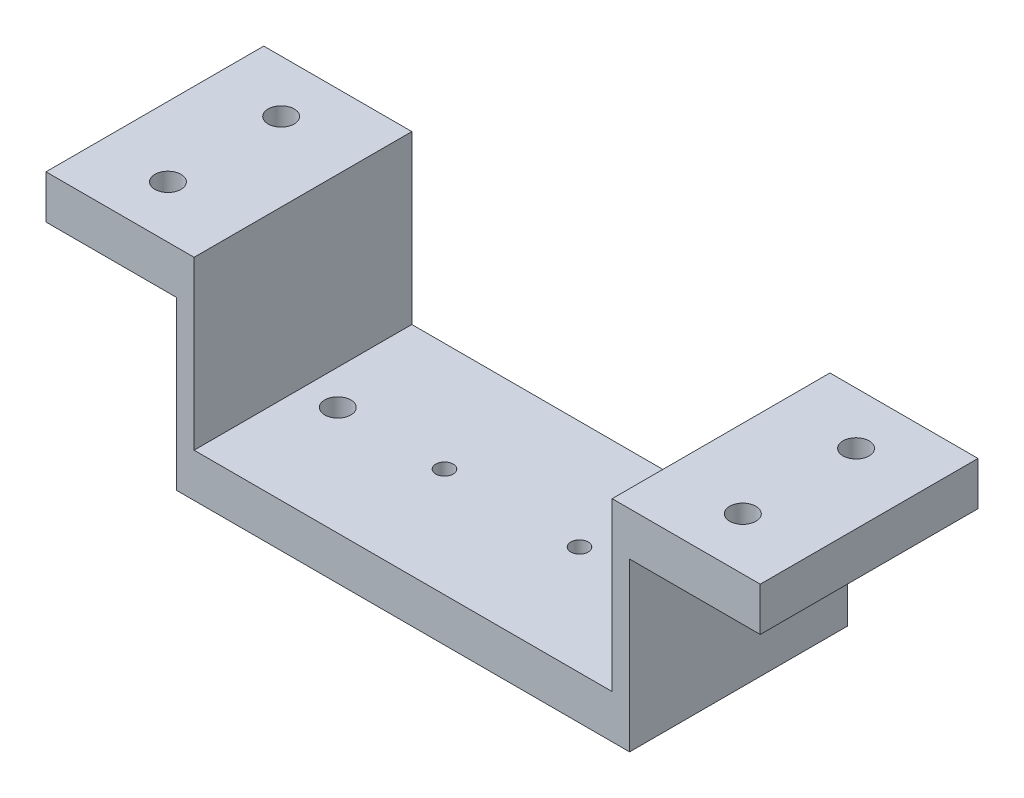
SolidWorks part; units mm, degrees
ref_plane "Front Plane" through (0, 0, 0) normal (0, 0, 1) x (1, 0, 0)
ref_plane "Top Plane" through (0, 0, 0) normal (0, 1, 0) x (1, 0, 0)
ref_plane "Right Plane" through (0, 0, 0) normal (1, 0, 0) x (0, 0, -1)
sketch "Sketch1" plane through (0, 0, 0) normal (0, 1, 0) x (1, 0, 0)
  line L1 (-26, -12.5) -> (26, -12.5)
  line L2 (-26, -12.5) -> (-26, 12.5)
  line L3 (-26, 12.5) -> (26, 12.5)
  line L4 (26, -12.5) -> (26, 12.5)
  line L5 (-26, -12.5) -> (26, 12.5) construction
  line L6 (-26, 12.5) -> (26, -12.5) construction
  point P0 (0, 0)
  dimension "D1" = 25
  dimension "D2" = 52
extrude "Boss-Extrude1" add sketch "Sketch1" along normal blind 24.18
sketch "Sketch4" plane through (0, 0, 12.5) normal (0, 0, 1) x (1, 0, 0)
  line L0 (-26, 0) -> (26, 0) construction
  line L1 (-24, 5) -> (24, 5)
  line L2 (-24, 5) -> (-24, 26.116)
  line L3 (-24, 26.116) -> (24, 26.116)
  line L4 (24, 5) -> (24, 26.116)
  line L5 (-24, 5) -> (24, 26.116) construction
  line L6 (-24, 26.116) -> (24, 5) construction
  line L8 (26, 24.18) -> (26, 0) construction
  line L10 (-26, 24.18) -> (-26, 0) construction
  point P0 (0, 15.558)
  dimension "D2" = 26
  dimension "D4" = 48
  dimension "D6" = 2
  dimension "D7" = 5
extrude "Cut-Extrude1" cut sketch "Sketch4" against normal blind 25
sketch "Sketch6" plane through (0, 0, 0) normal (0, -1, 0) x (1, 0, 0)
  line L0 (26, -12.5) -> (-26, -12.5) construction
  circle A0 centre (-7.75, 0) radius 1
  circle A1 centre (-20, 0) radius 1.5
  circle A2 centre (7.75, 0) radius 1
  circle A3 centre (20, 0) radius 1.5
  dimension "D1" = 3
  dimension "D2" = 2
  dimension "D3" = 2
  dimension "D4" = 3
  dimension "D5" = 7.75
  dimension "D6" = 7.75
  dimension "D7" = 12.25
  dimension "D8" = 12.25
  dimension "D9" = 12.5
  dimension "D10" = 12.5
  dimension "D11" = 12.5
  dimension "D12" = 12.5
extrude "Cut-Extrude5" cut sketch "Sketch6" against normal blind 24.18
sketch "Sketch8" plane through (26, 0, 0) normal (1, 0, 0) x (0, 0, -1)
  line L1 (-12.5, 24.18) -> (12.5, 24.18)
  line L2 (-12.5, 24.18) -> (-12.5, 19.18)
  line L3 (-12.5, 19.18) -> (12.5, 19.18)
  line L4 (12.5, 24.18) -> (12.5, 19.18)
  line L5 (-12.5, 24.18) -> (12.5, 19.18) construction
  line L6 (-12.5, 19.18) -> (12.5, 24.18) construction
  line L7 (12.5, 24.18) -> (12.5, 0) construction
  point P4 (0, 21.68)
  dimension "D1" = 5
  dimension "D2" = 25
extrude "Boss-Extrude2" add sketch "Sketch8" along normal blind 15
sketch "Sketch9" plane through (0, 24.18, 0) normal (0, 1, 0) x (1, 0, 0)
  line L0 (41, 12.5) -> (41, -12.5) construction
  line L2 (41, 12.5) -> (24, 12.5) construction
  circle A0 centre (33, 6.5) radius 1.5
  dimension "D1" = 3
  dimension "D2" = 8
  dimension "D3" = 6
extrude "Cut-Extrude7" cut sketch "Sketch9" against normal up to surface (5 mm away) up to face at (33.5, 19.18, 0)
mirror "Mirror3" about plane through (0, 0, 0) normal (0, 0, 1) of "Cut-Extrude7"
mirror "Mirror4" about plane through (0, 0, 0) normal (1, 0, 0) of "Boss-Extrude2", "Cut-Extrude7", "Mirror3"
